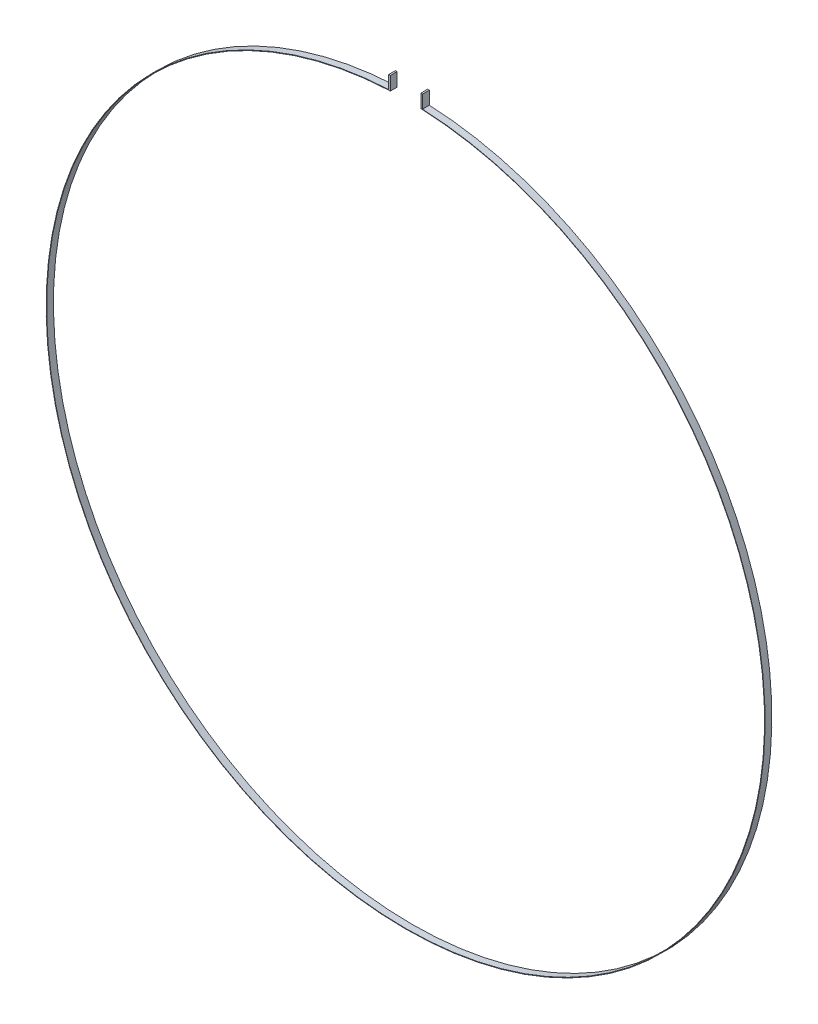
SolidWorks part; units mm, degrees
material "Stainless Steel (ferritic)"
ref_plane "Front Plane" through (0, 0, 0) normal (0, 0, 1) x (1, 0, 0)
ref_plane "Top Plane" through (0, 0, 0) normal (0, 1, 0) x (1, 0, 0)
ref_plane "Right Plane" through (0, 0, 0) normal (1, 0, 0) x (0, 0, -1)
sketch "Sketch1" plane through (0, 0, 0) normal (0, 0, 1) x (1, 0, 0)
  circle A0 centre (0, 0) radius 1060
  circle A1 centre (0, 0) radius 1061.5
  dimension "D1" = 2120
  dimension "D2" = 1.5
extrude "Boss-Extrude1" add sketch "Sketch1" along normal blind 20
sketch "Sketch2" plane through (0, 0, 0) normal (0, 0, 1) x (1, 0, 0)
  line L1 (50, 1098.8201) -> (-50, 1098.8201)
  line L2 (50, 1098.8201) -> (50, 1058.8201)
  line L3 (50, 1058.8201) -> (-50, 1058.8201)
  line L4 (-50, 1098.8201) -> (-50, 1058.8201)
  line L5 (50, 1098.8201) -> (-50, 1058.8201) construction
  line L6 (50, 1058.8201) -> (-50, 1098.8201) construction
  circle A0 centre (0, 0) radius 1060 construction
  point P0 (0, 1078.8201)
  dimension "D1" = 40
  dimension "D2" = 100
extrude "Boss-Extrude2" add sketch "Sketch2" along normal blind 20
sketch "Sketch3" plane through (0, 0, 20) normal (0, 0, 1) x (1, 0, 0)
  line L0 (50, 1060.3218) -> (50, 1098.8201) construction
  line L1 (-45, 1799.3934) -> (45, 1799.3934)
  line L2 (-45, 1799.3934) -> (-45, 942.4674)
  line L3 (-45, 942.4674) -> (45, 942.4674)
  line L4 (45, 1799.3934) -> (45, 942.4674)
  line L5 (-45, 1799.3934) -> (45, 942.4674) construction
  line L6 (-45, 942.4674) -> (45, 1799.3934) construction
  point P0 (0, 1370.9304)
  dimension "D1" = 5
extrude "Cut-Extrude1" cut sketch "Sketch3" against normal blind 40
